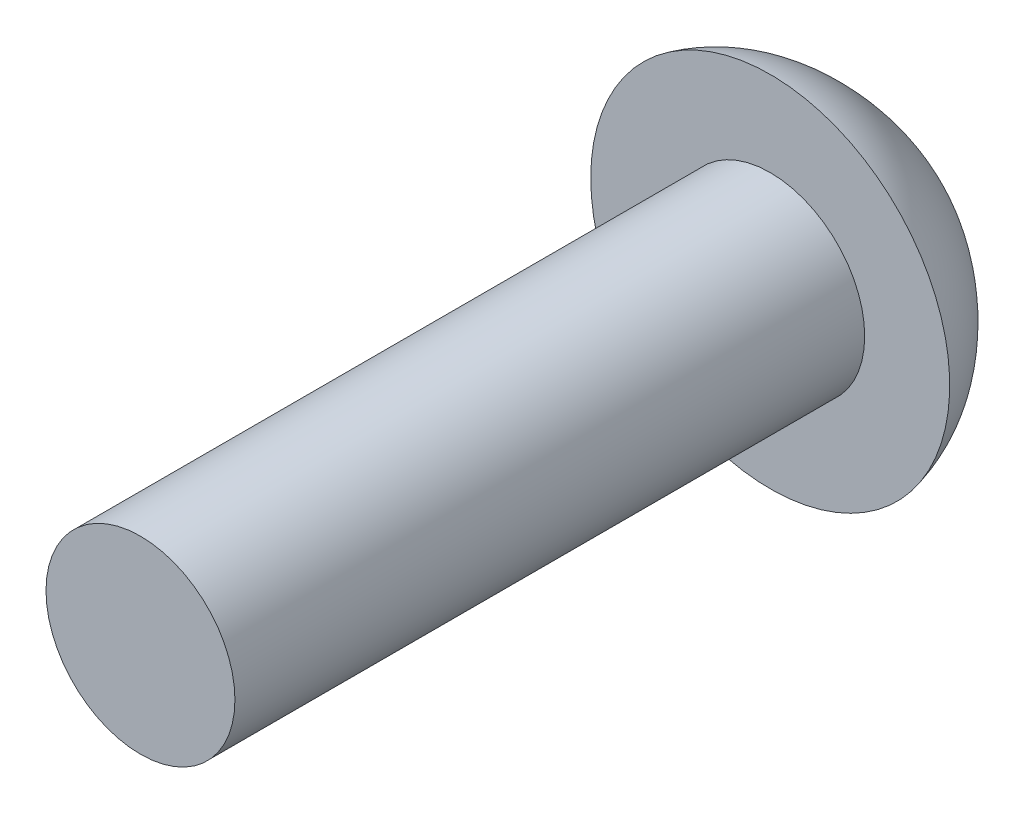
SolidWorks part; units mm, degrees
ref_plane "Front Plane" through (0, 0, 0) normal (0, 0, 1) x (1, 0, 0)
ref_plane "Top Plane" through (0, 0, 0) normal (0, 1, 0) x (1, 0, 0)
ref_plane "Right Plane" through (0, 0, 0) normal (1, 0, 0) x (0, 0, -1)
sketch "Sketch1" plane through (0, 0, 0) normal (0, 1, 0) x (1, 0, 0)
  line L0 (-367.694, 0) -> (18017.0074, 0) construction
  line L1 (0, -367.694) -> (0, 18017.0074) construction
  line L2 (1.5, 0) -> (1.5, 10)
  line L3 (1.5, 10) -> (2.85, 10)
  line L5 (1.5, 11.65) -> (0, 11.65)
  line L7 (0, 0) -> (1.5, 0)
  line L8 (0, 11.65) -> (0, 0)
  spline S0 degree 2 poles (1.5, 11.65) (2.6316, 10.9272) (2.85, 10) knots 0 0 0 0.488855 0.488855 0.488855
  dimension "D1" = 10
  dimension "D2" = 2.85
  dimension "D3" = 1.5
  dimension "D4" = 1.5
  dimension "D5" = 1.65
revolve "Revolve1" add sketch "Sketch1" angle 360 about L8
sketch "Sketch2" plane through (0, 0, -11.65) normal (0, 0, -1) x (-1, 0, 0)
  line L1 (0.5769, 1.0003) -> (-0.5778, 0.9997)
  line L2 (-0.5778, 0.9997) -> (-1.1547, -0.0005)
  line L3 (-1.1547, -0.0005) -> (-0.5769, -1.0003)
  line L4 (-0.5769, -1.0003) -> (0.5778, -0.9997)
  line L5 (0.5778, -0.9997) -> (1.1547, 0.0005)
  line L6 (1.1547, 0.0005) -> (0.5769, 1.0003)
  circle A0 centre (0, 0) radius 1 construction
  dimension "D1" = 2
extrude "Cut-Extrude1" cut sketch "Sketch2" against normal blind 1.5
